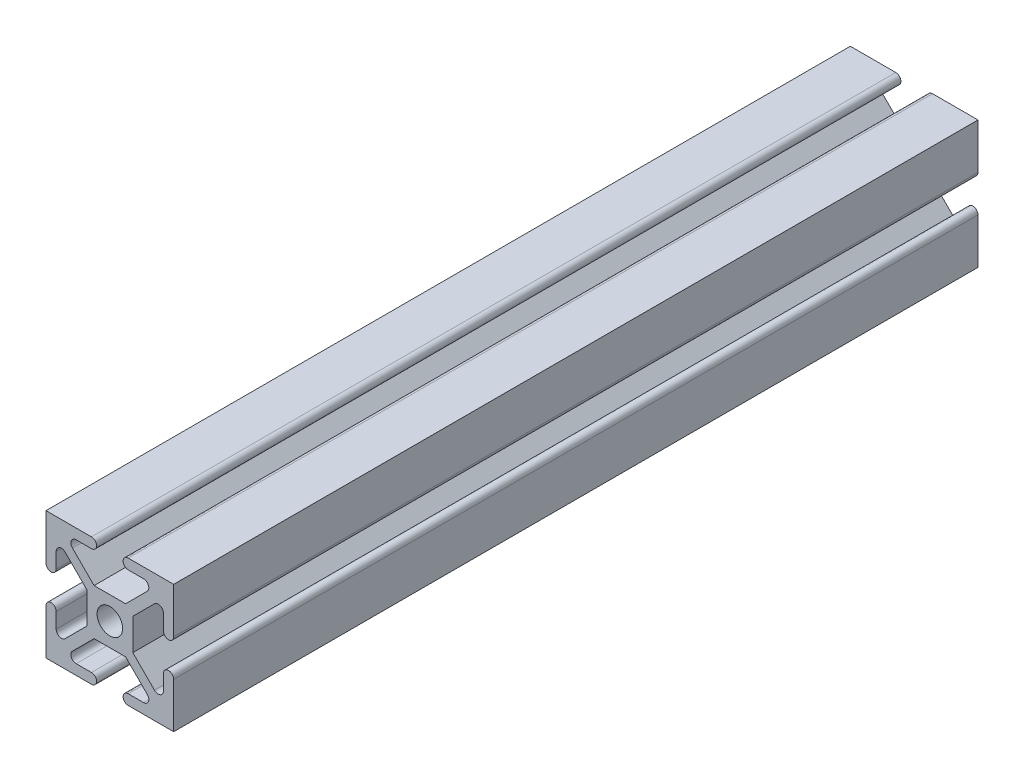
SolidWorks part; units mm, degrees
ref_plane "Front Plane" through (0, 0, 0) normal (0, 0, 1) x (1, 0, 0)
ref_plane "Top Plane" through (0, 0, 0) normal (0, 1, 0) x (1, 0, 0)
ref_plane "Right Plane" through (0, 0, 0) normal (1, 0, 0) x (0, 0, -1)
sketch "Sketch2" plane through (0, 0, 0) normal (0, 0, 1) x (1, 0, 0)
  line L0 (9.4142, 17) -> (5.1716, 21.2426)
  line L5 (9.4142, 17) -> (12.5, 17)
  line L9 (5.8995, 23) -> (8.8995, 23)
  line L10 (8.8995, 25) -> (0, 25)
  line L11 (0, 25) -> (8.8995, 25)
  line L12 (0, 16.1005) -> (0, 25)
  line L13 (2, 19.1005) -> (2, 16.1005)
  line L14 (8, 15.5858) -> (3.7574, 19.8284)
  line L15 (0, 25) -> (35355.3391, -35330.3391) construction
  line L16 (12.5, 12.5) -> (35367.8391, 35367.8391) construction
  line L17 (12.6363, 12.5) -> (50012.6363, 12.5) construction
  line L18 (12.5, 12.3637) -> (12.5, 50012.3637) construction
  line L19 (8, 15.5858) -> (8, 12.5)
  line L20 (9.4142, 8) -> (12.5, 8)
  line L21 (9.4142, 8) -> (5.1716, 3.7574)
  line L22 (5.8995, 2) -> (8.8995, 2)
  line L23 (8.8995, 0) -> (0, 0)
  line L24 (0, 8.8995) -> (0, 0)
  line L25 (2, 5.8995) -> (2, 8.8995)
  line L26 (8, 9.4142) -> (8, 12.5)
  line L27 (8, 9.4142) -> (3.7574, 5.1716)
  line L28 (15.5858, 17) -> (12.5, 17)
  line L29 (15.5858, 17) -> (19.8284, 21.2426)
  line L30 (19.1005, 23) -> (16.1005, 23)
  line L31 (16.1005, 25) -> (25, 25)
  line L32 (25, 16.1005) -> (25, 25)
  line L33 (23, 19.1005) -> (23, 16.1005)
  line L34 (17, 15.5858) -> (21.2426, 19.8284)
  line L35 (17, 15.5858) -> (17, 12.5)
  line L36 (17, 9.4142) -> (17, 12.5)
  line L37 (15.5858, 8) -> (12.5, 8)
  line L38 (17, 9.4142) -> (21.2426, 5.1716)
  line L39 (23, 5.8995) -> (23, 8.8995)
  line L40 (25, 8.8995) -> (25, 0)
  line L41 (16.1005, 0) -> (25, 0)
  line L42 (19.1005, 2) -> (16.1005, 2)
  line L43 (15.5858, 8) -> (19.8284, 3.7574)
  arc A0 (5.1716, 21.2426) -> (5.8995, 23) centre (5.8995, 21.9706) cw
  arc A1 (0, 16.1005) -> (2, 16.1005) centre (1, 16.1005) ccw
  arc A2 (8.8995, 25) -> (8.8995, 23) centre (8.8995, 24) cw
  arc A3 (3.7574, 19.8284) -> (2, 19.1005) centre (3.0294, 19.1005) ccw
  arc A4 (5.1716, 3.7574) -> (5.8995, 2) centre (5.8995, 3.0294) ccw
  arc A5 (8.8995, 0) -> (8.8995, 2) centre (8.8995, 1) ccw
  arc A6 (0, 8.8995) -> (2, 8.8995) centre (1, 8.8995) cw
  arc A7 (3.7574, 5.1716) -> (2, 5.8995) centre (3.0294, 5.8995) cw
  arc A8 (19.8284, 21.2426) -> (19.1005, 23) centre (19.1005, 21.9706) ccw
  arc A9 (16.1005, 25) -> (16.1005, 23) centre (16.1005, 24) ccw
  arc A10 (25, 16.1005) -> (23, 16.1005) centre (24, 16.1005) cw
  arc A11 (21.2426, 19.8284) -> (23, 19.1005) centre (21.9706, 19.1005) cw
  arc A12 (19.8284, 3.7574) -> (19.1005, 2) centre (19.1005, 3.0294) cw
  arc A13 (21.2426, 5.1716) -> (23, 5.8995) centre (21.9706, 5.8995) ccw
  arc A14 (25, 8.8995) -> (23, 8.8995) centre (24, 8.8995) ccw
  arc A15 (16.1005, 0) -> (16.1005, 2) centre (16.1005, 1) cw
  circle A16 centre (12.5, 12.5) radius 2.5
  dimension "D14" = 5
  dimension "D2" = 1.0294
  dimension "D3" = 12.5
  dimension "D4" = 12.5
  dimension "D5" = 17.6777
  dimension "D7" = 45
  dimension "D9" = 12.5
  dimension "D10" = 6
  dimension "D11" = 3
  dimension "D12" = 1
  dimension "D13" = 2
extrude "Boss-Extrude1" add sketch "Sketch2" along normal blind 157.5 contours A15 L41 L40 A14 L39 A13 L38 L36 L35 L34 A11 L33 A10 L32 L31 A9 L30 A8 L29 L28 L5 L0 A0 L9 A2 L10 L12 A1 L13 A3 L14 L19 L26 L27 A7 L25 A6 L24 L23 A5 L22 A4 L21 L20 L37 L43 A12 L42 A16
